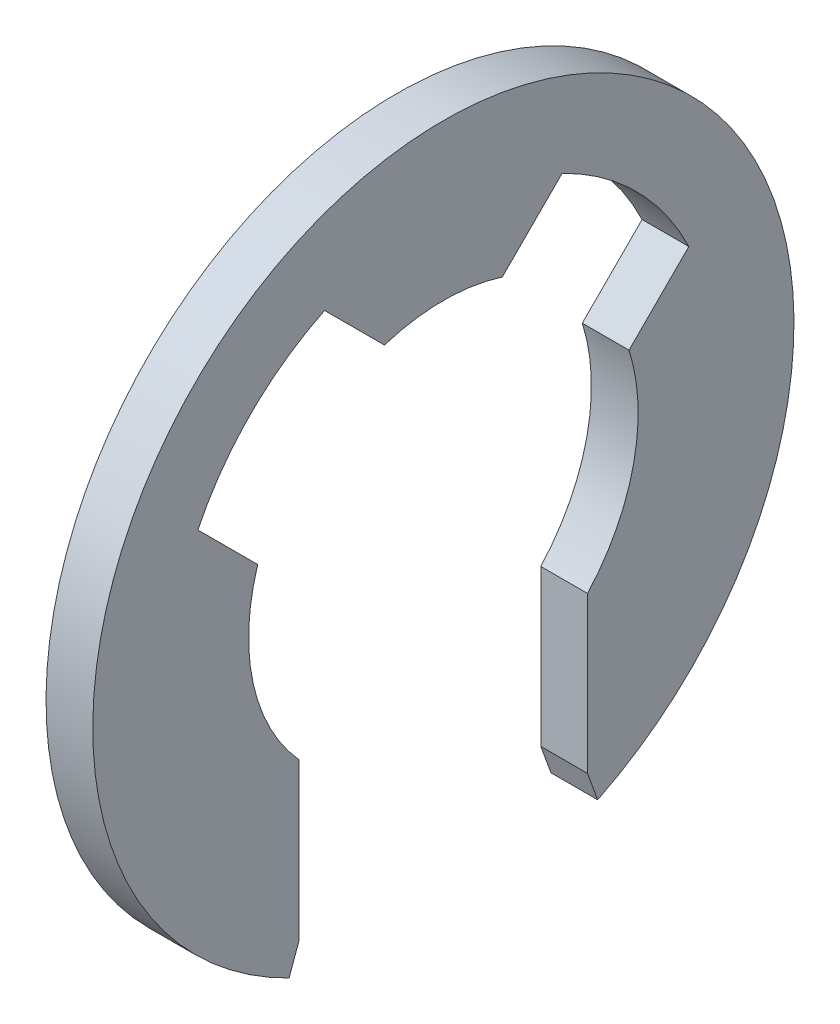
SolidWorks part; units mm, degrees
ref_plane "Face" through (0, 0, 0) normal (0, 0, 1) x (1, 0, 0)
ref_plane "Dessus" through (0, 0, 0) normal (0, 1, 0) x (1, 0, 0)
ref_plane "Droite" through (0, 0, 0) normal (1, 0, 0) x (0, 0, -1)
sketch "Esquisse1" plane through (0, 0, 0) normal (1, 0, 0) x (0, 0, -1)
  circle A0 centre (0, 0) radius 4.5
  dimension "D1" = 9
extrude "Base-Extrusion" add sketch "Esquisse1" along normal blind 0.6
sketch "Esquisse2" plane through (0.6, 0, 0) normal (1, 0, 0) x (0, 0, -1)
  line L0 (0, 4) -> (0, -4) construction
  line L1 (0, 0) -> (6, 6) construction
  line L2 (0, 0) -> (-6, 6) construction
  line L3 (0.7565, 2.3828) -> (1.5243, 3.1506)
  line L4 (2.3828, 0.7565) -> (3.1506, 1.5243)
  line L5 (-2.3828, 0.7565) -> (-3.1506, 1.5243)
  line L6 (-0.7565, 2.3828) -> (-1.5243, 3.1506)
  line L7 (1.85, -1.6815) -> (1.85, -3.6815)
  line L8 (-1.85, -1.6815) -> (-1.85, -3.6815)
  line L9 (1.85, -3.6815) -> (1.9807, -4.0406)
  line L10 (-1.85, -3.6815) -> (-1.9807, -4.0406)
  arc A0 (0.7565, 2.3828) -> (-0.7565, 2.3828) centre (0, 0) ccw
  arc A1 (-1.5243, 3.1506) -> (-3.1506, 1.5243) centre (0, 0) ccw
  arc A2 (-2.3828, 0.7565) -> (-1.85, -1.6815) centre (0, 0) ccw
  arc A3 (1.85, -1.6815) -> (2.3828, 0.7565) centre (0, 0) ccw
  arc A4 (3.1506, 1.5243) -> (1.5243, 3.1506) centre (0, 0) ccw
  circle A6 centre (0, 0) radius 4.5 construction
  arc A7 (-1.9807, -4.0406) -> (1.9807, -4.0406) centre (0, 0) ccw
  dimension "D1" = 2.5
  dimension "D2" = 7
  dimension "D7" = 2
  dimension "D3" = 2.3
  dimension "D4" = 45
  dimension "D5" = 3.7
  dimension "D6" = 160
extrude "Enlèv. mat.-Extru.1" cut sketch "Esquisse2" against normal through all
